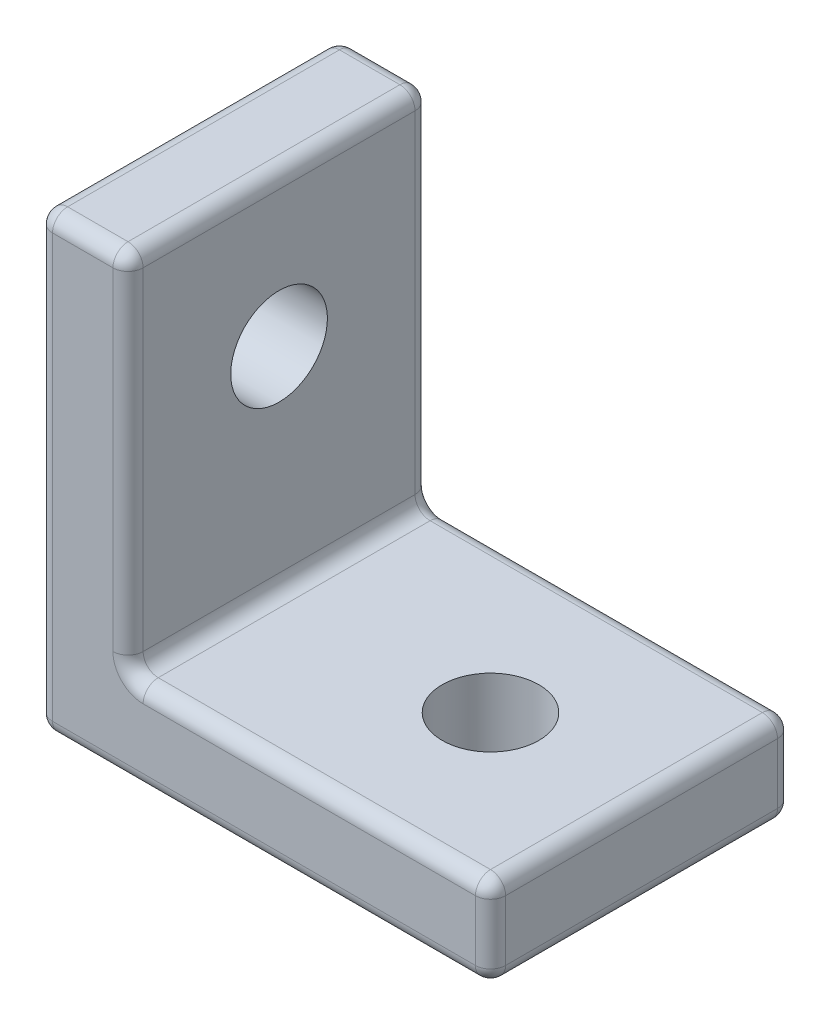
SolidWorks part; units mm, degrees
material "6061 合金"
ref_plane "Front Plane" through (0, 0, 0) normal (0, 0, 1) x (1, 0, 0)
ref_plane "Top Plane" through (0, 0, 0) normal (0, 1, 0) x (1, 0, 0)
ref_plane "Right Plane" through (0, 0, 0) normal (1, 0, 0) x (0, 0, -1)
other "Configuration Table"
sketch "草图1" plane through (0, 0, 0) normal (0, 0, 1) x (1, 0, 0)
  line L0 (0, 15) -> (0, 0)
  line L1 (0, 0) -> (15, 0)
  line L2 (15, 0) -> (15, 3)
  line L3 (15, 3) -> (3, 3)
  line L4 (3, 3) -> (3, 15)
  line L5 (3, 15) -> (0, 15)
  dimension "D1" = 3
  dimension "D2" = 3
  dimension "D3" = 15
  dimension "D4" = 15
extrude "凸台-拉伸1" add sketch "草图1" along normal blind 10
sketch "草图2" plane through (0, 0, 0) normal (-1, 0, 0) x (0, 0, 1)
  line L0 (10, 15) -> (0, 15) construction
  line L1 (0, 15) -> (0, 0) construction
  circle A0 centre (5, 10) radius 1.6
  dimension "D1" = 5
  dimension "D3" = 3.2
  dimension "D2" = 5
sketch "草图3" plane through (0, 0, 0) normal (0, -1, 0) x (1, 0, 0)
  line L0 (0, 10) -> (15, 10) construction
  line L1 (0, 6.6) -> (0, 3.4) construction
  circle A0 centre (10, 5) radius 1.6
  dimension "D1" = 5
  dimension "D3" = 3.2
  dimension "D2" = 10
extrude "切除-拉伸1" cut sketch "草图3" against normal blind 5
extrude "切除-拉伸2" cut sketch "草图2" against normal blind 5
fillet "圆角1" radius 0.5 18 edges at (1.5, 15, 0) (0, 7.5, 0) (7.5, 0, 0) (15, 1.5, 0) (9, 3, 0) (3, 9, 0) (1.5, 15, 10) (0, 7.5, 10) (7.5, 0, 10) (15, 1.5, 10) (9, 3, 10) (3, 9, 10) (15, 3, 5) (15, 0, 5) (0, 0, 5) (0, 15, 5) (3, 15, 5) (3, 3, 5)
thread "螺纹线1" pitch 0.45 start angle 0, offset 0, length 10, pitch 0.45, diameter 3.2
ref_plane "基准面1" through (5.9, 3, 5) normal (0, 0, 1) x (-1, 0, 0)
sketch "螺纹线轮廓1" plane through (5.9, 3, 5) normal (0, 0, 1) x (-1, 0, 0)
  line L0 (0, 0) -> (0, 0.45) construction
  line L1 (0, 0) -> (0.2436, 0.1406)
  line L2 (0.2436, 0.1406) -> (0.2436, 0.1969)
  line L3 (0.2436, 0.1969) -> (0, 0.3375)
  line L4 (0.2436, 0.1687) -> (0, 0.1687) construction
  line L11 (0, 0) -> (0, 0.3375)
  point P2 (0, 0)
  dimension "Pitch" = 0.45
  dimension "Profile_Angle" = 60
  dimension "Profile_Land" = 0.0562
  dimension "Profile_Height" = 0.2436
thread "螺纹线2" pitch 0.45 start angle 0, offset 0, length 10, pitch 0.45, diameter 3.2
ref_plane "基准面2" through (3, 7.5, 6.6) normal (0, -1, 0) x (0, 0, 1)
sketch "螺纹线轮廓2" plane through (3, 7.5, 6.6) normal (0, -1, 0) x (0, 0, 1)
  line L0 (0, 0) -> (0, 0.45) construction
  line L1 (0, 0) -> (0.2436, 0.1406)
  line L2 (0.2436, 0.1406) -> (0.2436, 0.1969)
  line L3 (0.2436, 0.1969) -> (0, 0.3375)
  line L4 (0.2436, 0.1687) -> (0, 0.1687) construction
  line L11 (0, 0) -> (0, 0.3375)
  point P2 (0, 0)
  dimension "Pitch" = 0.45
  dimension "Profile_Angle" = 60
  dimension "Profile_Land" = 0.0562
  dimension "Profile_Height" = 0.2436
sketch "Sketch1" plane through (0, 0, 0) normal (-1, 0, 0) x (0, 0, 1)
  line B0 (0, 15) -> (0, 0)
  line B1 (0, 0) -> (10, 0)
  line B2 (10, 0) -> (10, 15)
  line B3 (10, 15) -> (0, 15)
  circle B4 centre (5, 10) radius 1.6
sketch_block_instance "Block1-1"
sketch_block "Block1"
